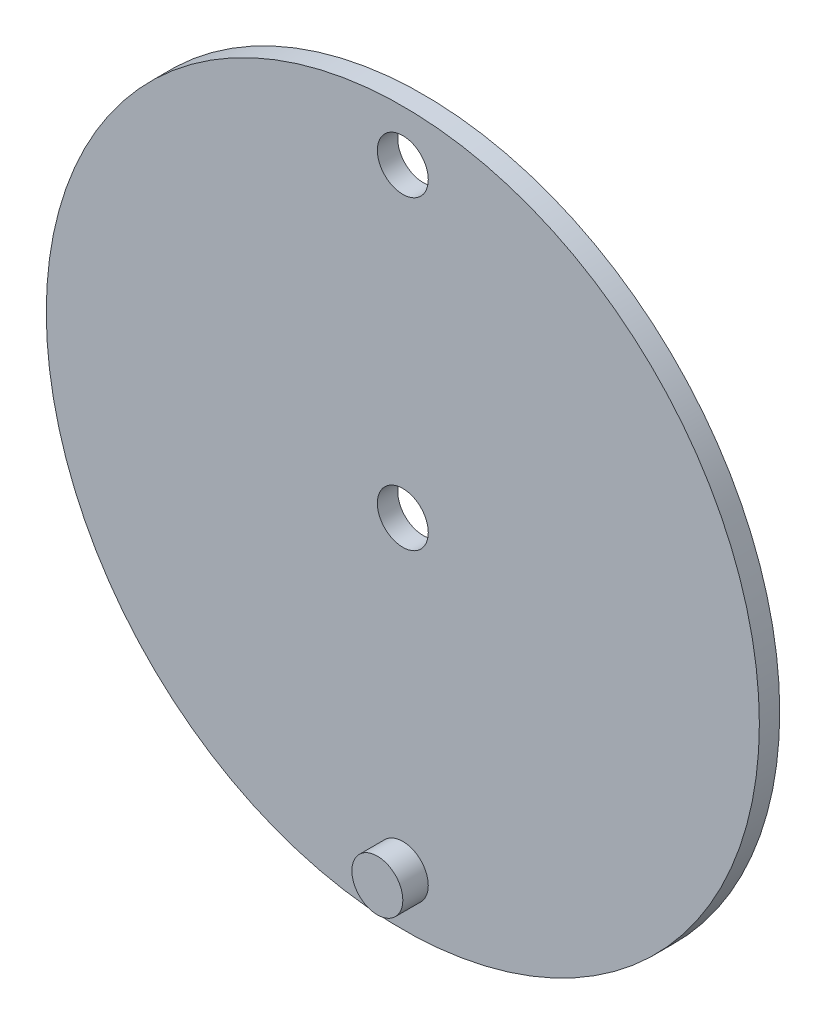
SolidWorks part; units mm, degrees
ref_plane "Front Plane" through (0, 0, 0) normal (0, 0, 1) x (1, 0, 0)
ref_plane "Top Plane" through (0, 0, 0) normal (0, 1, 0) x (1, 0, 0)
ref_plane "Right Plane" through (0, 0, 0) normal (1, 0, 0) x (0, 0, -1)
sketch "Sketch1" plane through (0, 0, 0) normal (0, 0, 1) x (1, 0, 0)
  line L0 (-169.7289, -88.9) -> (169.7289, -88.9) construction
  line L1 (-97.9706, 88.9) -> (97.9706, 88.9) construction
  circle A0 centre (0, 0) radius 88.9
  circle A1 centre (0, 0) radius 6.35
  circle A2 centre (0, -76.2) radius 6.35
  circle A3 centre (0, 76.2) radius 6.35
  point P7 (0, -88.9)
  point P14 (0, 88.9)
  dimension "D1" = 177.8
  dimension "D2" = 12.7
  dimension "D3" = 12.7
  dimension "D5" = 12.7
  dimension "D4" = 12.7
  dimension "D6" = 12.7
extrude "Boss-Extrude1" add sketch "Sketch1" along normal blind 5.08
sketch "Sketch2" plane through (0, 0, 0) normal (0, 0, 1) x (1, 0, 0)
  circle A0 centre (0, -76.2) radius 6.35
extrude "Boss-Extrude2" add sketch "Sketch2" along normal blind 11.43
